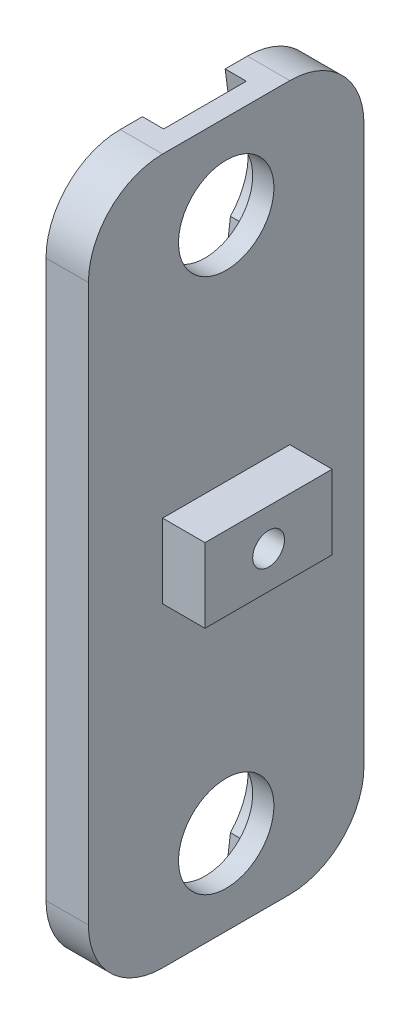
SolidWorks part; units mm, degrees
ref_plane "Спереди" through (0, 0, 0) normal (0, 0, 1) x (1, 0, 0)
ref_plane "Сверху" through (0, 0, 0) normal (0, 1, 0) x (1, 0, 0)
ref_plane "Справа" through (0, 0, 0) normal (1, 0, 0) x (0, 0, -1)
ref_plane "Плоскость4" through (0, 0, 0) normal (-1, 0, 0) x (0, -1, 0)
sketch "Эскиз1" plane through (0, 0, 0) normal (-1, 0, 0) x (0, -1, 0)
  line L0 (17.5, -13) -> (17.5, 13)
  line L1 (17.5, 13) -> (-19.25, 13)
  line L2 (-19.25, 13) -> (-19.25, -13)
  line L3 (-19.25, -13) -> (17.5, -13)
  dimension "D1" = 36.75
  dimension "D2" = 26
extrude "Бобышка-Вытянуть1" add sketch "Эскиз1" against normal blind 4
sketch "Эскиз2" plane through (0, 0, 0) normal (-1, 0, 0) x (0, 0, 1)
  line L0 (3.9012, -17.5) -> (4.5455, -13.6524)
  line L1 (4.5455, -5.2103) -> (2.7955, 8.2897)
  line L2 (-2.65, 8.2897) -> (-4.4, -5.2103)
  line L3 (-4.4, -13.6524) -> (-3.9012, -17.5)
  line L4 (-3.9012, -17.5) -> (3.9012, -17.5)
  arc A0 (4.5455, -13.6524) -> (4.5455, -5.2103) centre (0.0727, -9.4314) ccw
  arc A1 (2.7955, 8.2897) -> (-2.65, 8.2897) centre (0.0727, 8.2897) ccw
  arc A2 (-4.4, -5.2103) -> (-4.4, -13.6524) centre (0.0727, -9.4314) ccw
extrude "Вырез-Вытянуть1" cut sketch "Эскиз2" against normal blind 2
sketch "Эскиз3" plane through (0, 0, 13) normal (0, 0, 1) x (1, 0, 0)
  line L0 (8, 12.25) -> (4, 12.25)
  line L1 (4, 12.25) -> (4, -17.5)
  line L2 (4, -17.5) -> (8, -17.5)
  line L3 (8, -17.5) -> (8, 12.25)
  dimension "D1" = 29.75
fillet "Скругление1" radius 7 2 edges at (2, -17.5, -13) (2, -17.5, 13)
sketch "Эскиз9" plane through (2, 0, 0) normal (-1, 0, 0) x (0, 0, 1)
  line L0 (0, -17.5) -> (0, -9.5) construction
  line L1 (-3.9012, -17.5) -> (3.9012, -17.5) construction
  line L2 (0, -9.5) -> (13, -9.5)
  line L4 (13, -17.5) -> (13, 12.25) construction
  circle A0 centre (0, -9.5) radius 4.5
  dimension "D3" = 9
  dimension "D1" = 8
  dimension "D2" = 13
extrude "Вырез-Вытянуть3" cut sketch "Эскиз9" against normal up to surface (2 mm away) contours A0 L0 L2 | L0 A0 L2 up to face at (4, -3.3999, 0)
sketch "Эскиз11" plane through (4, 0, 0) normal (1, 0, 0) x (0, 0, -1)
  line L0 (0, 19.25) -> (0, 12.25) construction
  line L1 (-13, 19.25) -> (13, 19.25) construction
  line L2 (-6, 12.25) -> (6, 12.25) construction
  line L4 (-6, 12.25) -> (6, 12.25)
  line L5 (-6, 12.25) -> (-6, 19.25)
  line L6 (-6, 19.25) -> (6, 19.25)
  line L7 (6, 12.25) -> (6, 19.25)
  point P8 (0, 12.25)
  dimension "D1" = 7
  dimension "D2" = 7
  dimension "D3" = 6
  dimension "D4" = 12
extrude "Бобышка-Вытянуть2" add sketch "Эскиз11" along normal blind 4
sketch "Эскиз12" plane through (0, 0, 0) normal (-1, 0, 0) x (0, 0, 1)
  line L0 (0, 19.25) -> (0, 15.75) construction
  line L1 (13, 19.25) -> (-13, 19.25) construction
  circle A0 centre (0, 15.75) radius 1.5
  dimension "D2" = 3
  dimension "D1" = 3.5
extrude "Вырез-Вытянуть4" cut sketch "Эскиз12" against normal up to surface (8 mm away) up to face at (8, 15.75, 0)
sketch "Эскиз13" plane through (0, 0, 0) normal (-1, 0, 0) x (0, 0, 1)
  circle A0 centre (0, 15.75) radius 2.75
  dimension "D1" = 5.5
extrude "Вырез-Вытянуть5" cut sketch "Эскиз13" against normal blind 1
ref_plane "Плоскость6" through (0, 15.75, 0) normal (0, 1, 0) x (1, 0, 0)
mirror "Зеркальное отражение2" about plane through (0, 15.75, 0) normal (0, 1, 0) of "Вырез-Вытянуть5", "Вырез-Вытянуть4", "Бобышка-Вытянуть2", "Вырез-Вытянуть3", "Скругление1", "Вырез-Вытянуть1", "Бобышка-Вытянуть1"
